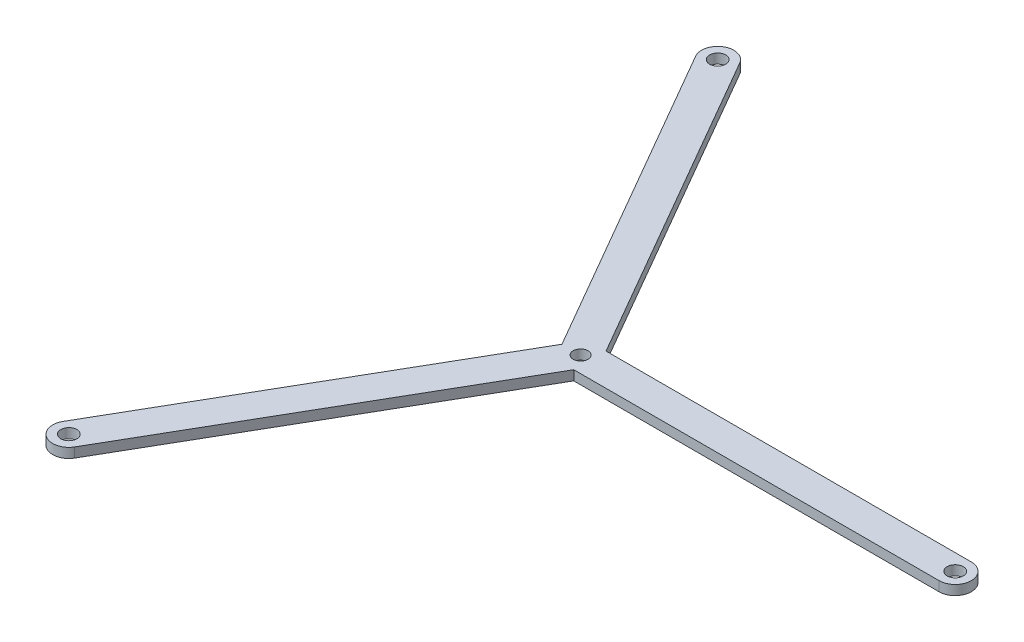
SolidWorks part; units mm, degrees
ref_plane "Front Plane" through (0, 0, 0) normal (0, 0, 1) x (1, 0, 0)
ref_plane "Top Plane" through (0, 0, 0) normal (0, 1, 0) x (1, 0, 0)
ref_plane "Right Plane" through (0, 0, 0) normal (1, 0, 0) x (0, 0, -1)
sketch "Sketch8" plane through (0, 0, 0) normal (0, 1, 0) x (1, 0, 0)
  line L0 (0, 0) -> (116, 0) construction
  line L1 (0, 5) -> (116, 5)
  line L2 (0, -5) -> (116, -5)
  line L3 (-4.3301, 2.5) -> (-62.3301, -97.9589)
  line L4 (4.3301, -2.5) -> (-53.6699, -102.9589)
  line L5 (0, 0) -> (-58, -100.4589) construction
  line L6 (4.3301, 2.5) -> (-53.6699, 102.9589)
  line L7 (-4.3301, -2.5) -> (-62.3301, 97.9589)
  line L8 (0, 0) -> (-58, 100.4589) construction
  circle A0 centre (0, 0) radius 2.3
  arc A1 (0, 5) -> (0, -5) centre (0, 0) ccw
  circle A3 centre (116, 0) radius 2.5
  arc A4 (116, -5) -> (116, 5) centre (116, 0) ccw
  arc A6 (4.3301, -2.5) -> (-4.3301, 2.5) centre (0, 0) ccw
  arc A7 (-62.3301, -97.9589) -> (-53.6699, -102.9589) centre (-58, -100.4589) ccw
  circle A8 centre (-58, -100.4589) radius 2.5
  arc A9 (-4.3301, -2.5) -> (4.3301, 2.5) centre (0, 0) ccw
  arc A10 (-53.6699, 102.9589) -> (-62.3301, 97.9589) centre (-58, 100.4589) ccw
  circle A11 centre (-58, 100.4589) radius 2.5
  point P9 (58, 0)
  point P19 (-29, -50.2295)
  point P26 (-29, 50.2295)
  point P31 (0, 0)
  dimension "D2" = 5
  dimension "D3" = 5
  dimension "D4" = 3
extrude "Boss-Extrude5" add sketch "Sketch8" along normal blind 3 separate body contours L6 A10 L7 L3 A1 L1 A11 | A6 L4 L2 A4 L1 L6 A3 | L3 A7 L4 L2 A1 L7 A8 | A1 A9 A6 A0 | A6 L6 L1 | A1 L3 L7 | A9 L2 L4
